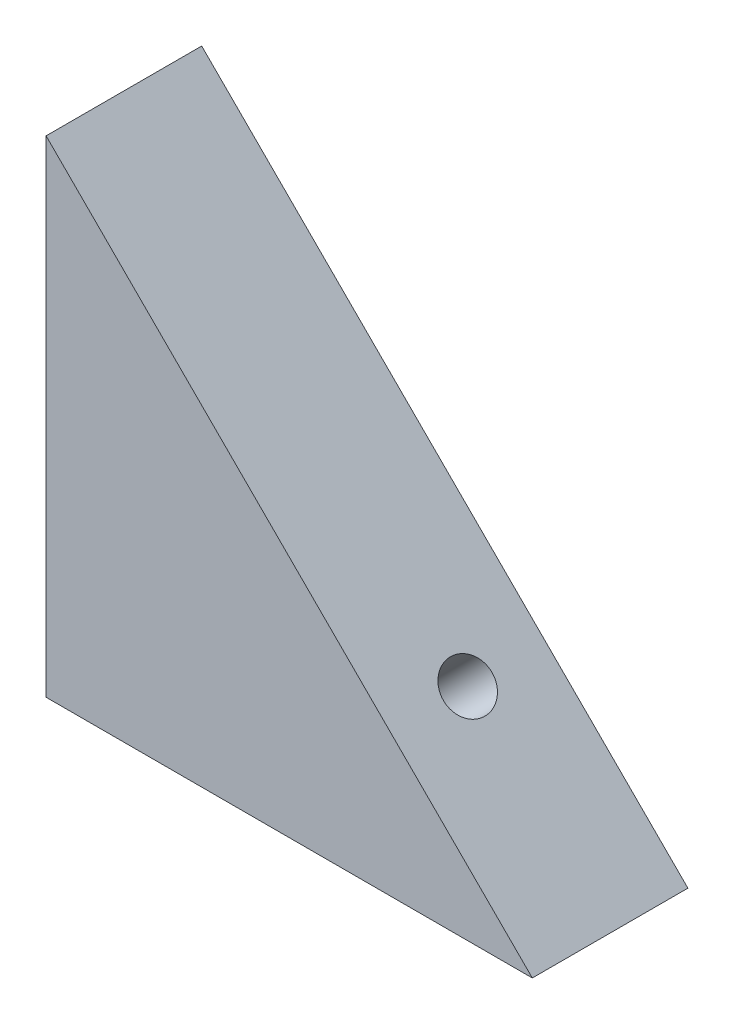
SolidWorks part; units mm, degrees
ref_plane "前视基准面" through (0, 0, 0) normal (0, 0, 1) x (1, 0, 0)
ref_plane "上视基准面" through (0, 0, 0) normal (0, 1, 0) x (1, 0, 0)
ref_plane "右视基准面" through (0, 0, 0) normal (1, 0, 0) x (0, 0, -1)
sketch "草图1" plane through (0, 0, 0) normal (0, 0, 1) x (1, 0, 0)
  line L0 (-42.303, -7.2358) -> (-42.303, -32.2358)
  line L1 (-42.303, -32.2358) -> (-17.303, -32.2358)
  line L2 (-17.303, -32.2358) -> (-42.303, -7.2358)
  dimension "D1" = 45
  dimension "D2" = 25
extrude "凸台-拉伸2" add sketch "草图1" along normal blind 8
hole_wizard "M3 螺纹孔2" positions "草图6" profile "草图7" tap size "M3" standard "GB"
sketch "草图6" plane through (-24.7694, -24.7694, 0) normal (0.7071, 0.7071, 0) x (0.7071, -0.7071, 0)
  line L0 (10.5591, 0) -> (-24.7962, 0) construction
  line L1 (-24.7962, -8) -> (-24.7962, 0) construction
  point P0 (0.2038, -4)
  dimension "D1" = 4
  dimension "D2" = 25
sketch "草图7" plane through (-24.6253, -24.9135, 4) normal (0, 0, 1) x (-0.7071, 0.7071, 0)
  line L0 (0, 0) -> (0, 5)
  line L1 (0, 5) -> (1.25, 5)
  line L2 (1.25, 5) -> (1.25, 0)
  line L5 (1.25, 0) -> (0, 0)
  line L10 (0, 5) -> (-1.25, 5) construction
  line L11 (0, -6.35) -> (0, 107.95) construction
  dimension "螺纹孔钻头直径" = 2.5
  dimension "螺纹孔钻头深度" = 5
  dimension "导头角度" = 180
cosmetic thread "孔螺蚊线2" parameters "D1"=5, "D2"=3
